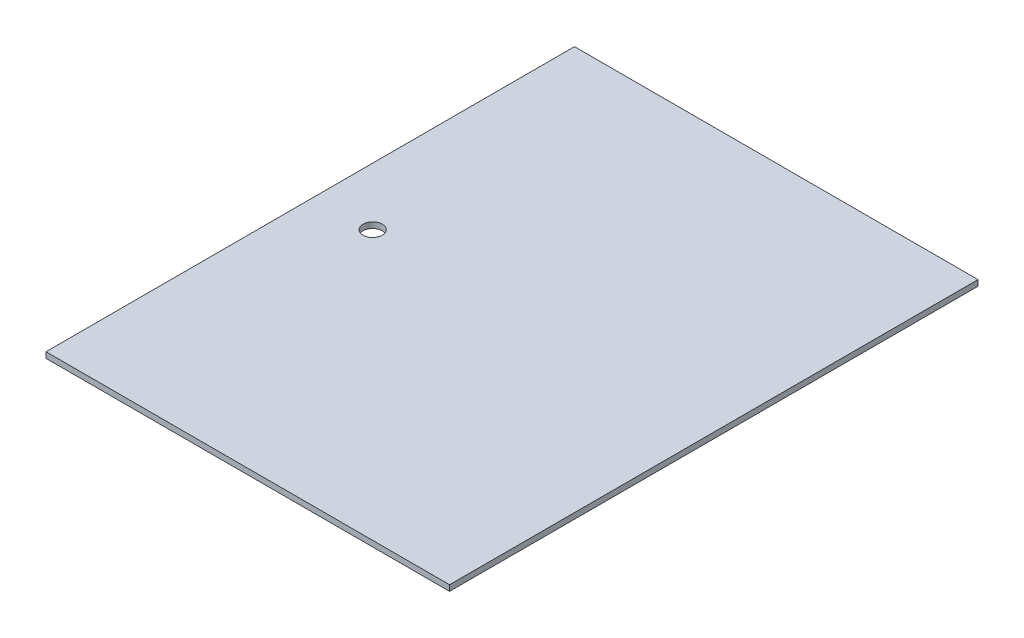
SolidWorks part; units mm, degrees
ref_plane "Front Plane" through (0, 0, 0) normal (0, 0, 1) x (1, 0, 0)
ref_plane "Top Plane" through (0, 0, 0) normal (0, 1, 0) x (1, 0, 0)
ref_plane "Right Plane" through (0, 0, 0) normal (1, 0, 0) x (0, 0, -1)
sketch "Sketch1" plane through (0, 0, 0) normal (0, 1, 0) x (1, 0, 0)
  line L1 (-74.7122, 199.4786) -> (135.2878, 199.4786)
  line L2 (-74.7122, 199.4786) -> (-74.7122, -75.5214)
  line L3 (-74.7122, -75.5214) -> (135.2878, -75.5214)
  line L4 (135.2878, 199.4786) -> (135.2878, -75.5214)
extrude "Boss-Extrude1" add sketch "Sketch1" along normal blind 3
sketch "Sketch2" plane through (0, 3, 0) normal (0, 1, 0) x (1, 0, 0)
  line L0 (-74.7122, 199.4786) -> (-74.7122, -75.5214) construction
  line L1 (135.2878, 199.4786) -> (-74.7122, 199.4786) construction
  circle A0 centre (-44.7122, 64.4786) radius 5
  dimension "D1" = 30
  dimension "D2" = 135
extrude "Cut-Extrude1" cut sketch "Sketch2" against normal blind 3 contours A0
